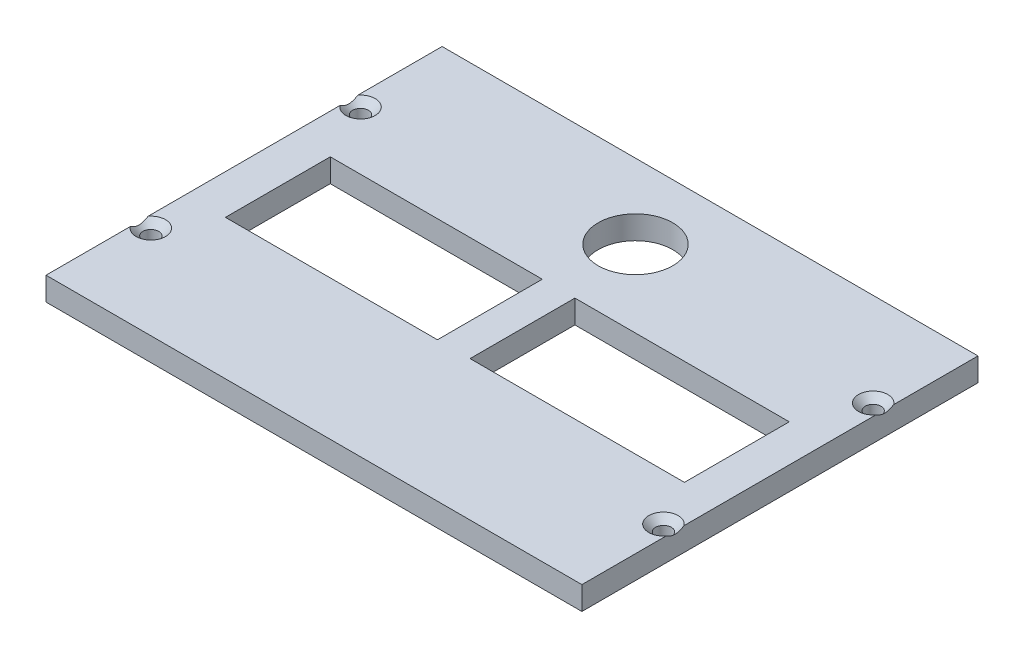
SolidWorks part; units mm, degrees
material "Acrylic"
ref_plane "Front" through (0, 0, 0) normal (0, 0, 1) x (1, 0, 0)
ref_plane "Top" through (0, 0, 0) normal (0, 1, 0) x (1, 0, 0)
ref_plane "Right" through (0, 0, 0) normal (1, 0, 0) x (0, 0, -1)
sketch "Sketch1" plane through (0, 0, 0) normal (0, 1, 0) x (1, 0, 0)
  line L1 (0, 0) -> (115, 0)
  line L2 (0, 0) -> (0, 85)
  line L3 (0, 85) -> (115, 85)
  line L4 (115, 0) -> (115, 85)
  line L5 (8.5, 52.5) -> (54, 52.5)
  line L6 (8.5, 52.5) -> (8.5, 30)
  line L7 (8.5, 30) -> (54, 30)
  line L8 (54, 52.5) -> (54, 30)
  line L9 (61, 52.5) -> (107, 52.5)
  line L10 (61, 52.5) -> (61, 30)
  line L11 (61, 30) -> (107, 30)
  line L12 (107, 52.5) -> (107, 30)
  circle A0 centre (57.5, 69) radius 8
  dimension "D9" = 16
  dimension "D11" = 69
  dimension "D1" = 85
  dimension "D2" = 115
  dimension "D3" = 8.5
  dimension "D4" = 54
  dimension "D5" = 61
  dimension "D6" = 107
  dimension "D7" = 30
  dimension "D8" = 52.5
  dimension "D10" = 57.5
  dimension "D12" = 30
  dimension "D13" = 52.5
extrude "Boss-Extrude1" add sketch "Sketch1" against normal blind 5
hole_wizard "CSK for M3 Flat Countersunk Head Screw1" positions "Sketch2" profile "Sketch3" countersink size "M3" standard "JIS" end condition through all
sketch "Sketch2" plane through (0, 0, 0) normal (0, 1, 0) x (1, 0, 0)
  line L0 (0, 85) -> (0, 0) construction
  line L1 (0, 0) -> (115, 0) construction
  point P0 (2.5, 65)
  point P2 (2.5, 20)
  point P4 (112.5, 65)
  point P6 (112.5, 20)
  dimension "D1" = 2.5
  dimension "D2" = 112.5
  dimension "D3" = 20
  dimension "D4" = 65
sketch "Sketch3" plane through (2.5, 0, -65) normal (1, 0, 0) x (0, 0, 1)
  line L0 (0, 0) -> (0, 5)
  line L1 (0, 5) -> (1.7, 5)
  line L2 (1.7, 5) -> (1.7, 1.45)
  line L3 (1.7, 1.45) -> (3.15, 0)
  line L5 (3.15, 0) -> (0, 0)
  line L6 (-1.7, 1.45) -> (-3.15, 0) construction
  line L11 (0, -6.35) -> (0, 107.95) construction
  dimension "Thru Hole Dia." = 3.4
  dimension "Thru Hole Depth" = 5
  dimension "Near C'Sink Dia." = 6.3
  dimension "Near C'Sink Angle" = 90
